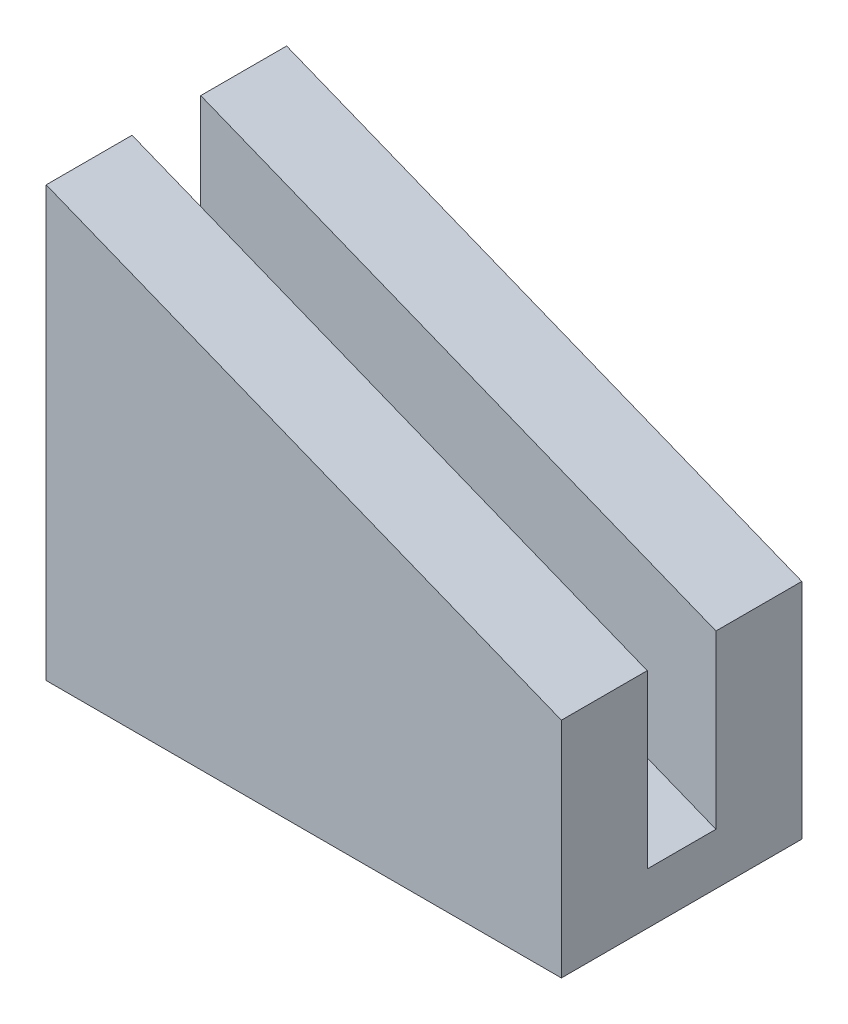
SolidWorks part; units mm, degrees
ref_plane "Front Plane" through (0, 0, 0) normal (0, 0, 1) x (1, 0, 0)
ref_plane "Top Plane" through (0, 0, 0) normal (0, 1, 0) x (1, 0, 0)
ref_plane "Right Plane" through (0, 0, 0) normal (1, 0, 0) x (0, 0, -1)
sketch "Sketch1" plane through (0, 0, 0) normal (0, 1, 0) x (1, 0, 0)
  line L1 (-38.1, 17.78) -> (38.1, 17.78)
  line L2 (-38.1, 17.78) -> (-38.1, -17.78)
  line L3 (-38.1, -17.78) -> (38.1, -17.78)
  line L4 (38.1, 17.78) -> (38.1, -17.78)
  line L5 (-38.1, 17.78) -> (38.1, -17.78) construction
  line L6 (-38.1, -17.78) -> (38.1, 17.78) construction
  point P0 (0, 0)
  dimension "D1" = 35.56
  dimension "D2" = 76.2
extrude "Boss-Extrude1" add sketch "Sketch1" along normal blind 63.5
sketch "Sketch2" plane through (0, 63.5, 0) normal (0, 1, 0) x (1, 0, 0)
  line L0 (38.1, -17.78) -> (38.1, 17.78) construction
  line L1 (-38.1, 5.08) -> (38.1, 5.08)
  line L2 (-38.1, 5.08) -> (-38.1, -5.08)
  line L3 (-38.1, -5.08) -> (38.1, -5.08)
  line L4 (38.1, 5.08) -> (38.1, -5.08)
  line L5 (-38.1, 5.08) -> (38.1, -5.08) construction
  line L6 (-38.1, -5.08) -> (38.1, 5.08) construction
  point P0 (0, 0)
  dimension "D1" = 10.16
extrude "Cut-Extrude1" cut sketch "Sketch2" against normal blind 25.4
sketch "Sketch3" plane through (0, 0, -5.08) normal (0, 0, 1) x (1, 0, 0)
  line L2 (-38.1, 63.5) -> (-38.1, 0) construction
  line L5 (38.1, 7.62) -> (38.1, 38.1)
  line L7 (38.1, 38.1) -> (-38.1, 38.1)
  line L9 (38.1, 7.62) -> (-38.1, 38.1)
  dimension "D1" = 7.62
extrude "Cut-Extrude2" cut sketch "Sketch3" along normal up to surface (10.16 mm away) up to face at (0, 50.8, 5.08)
sketch "Sketch4" plane through (0, 0, 5.08) normal (0, 0, -1) x (-1, 0, 0)
  line L0 (38.1, 63.5) -> (-38.1, 33.02)
  line L1 (38.1, 38.1) -> (38.1, 63.5) construction
  line L2 (-38.1, 7.62) -> (-38.1, 63.5) construction
  line L3 (38.1, 38.1) -> (-38.1, 7.62) construction
  line L4 (38.1, 63.5) -> (-38.1, 63.5) construction
  line L5 (-38.1, 33.02) -> (-38.1, 63.5)
  line L6 (-38.1, 63.5) -> (38.1, 63.5)
extrude "Cut-Extrude3" cut sketch "Sketch4" against normal through all both and the other way through all
